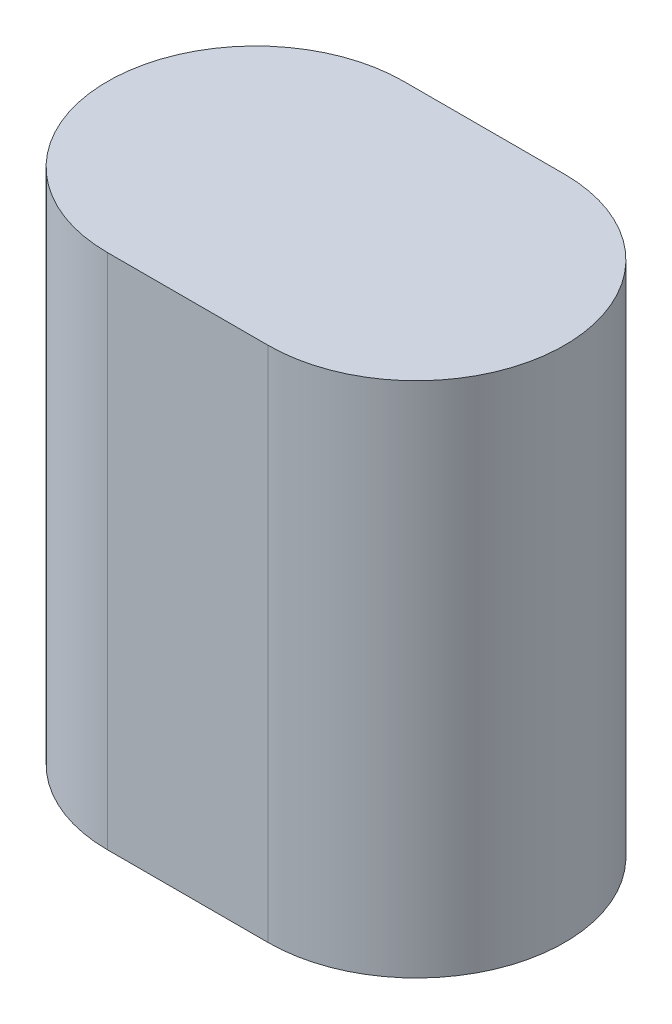
SolidWorks part; units mm, degrees
ref_plane "Front Plane" through (0, 0, 0) normal (0, 0, 1) x (1, 0, 0)
ref_plane "Top Plane" through (0, 0, 0) normal (0, 1, 0) x (1, 0, 0)
ref_plane "Right Plane" through (0, 0, 0) normal (1, 0, 0) x (0, 0, -1)
sketch "Sketch3" plane through (0, 0, 0) normal (0, 1, 0) x (1, 0, 0)
  line L0 (-8, 0) -> (8, 0) construction
  line L1 (-8, 14.7556) -> (8, 14.7557)
  line L2 (-8, -14.7556) -> (8, -14.7556)
  arc A0 (-8, 14.7556) -> (-8, -14.7556) centre (-8, 0) ccw
  arc A1 (8, -14.7556) -> (8, 14.7557) centre (8, 0) ccw
  point P2 (0, 0)
  dimension "D2" = 16
  dimension "D1" = 29.5113
extrude "Boss-Extrude1" add sketch "Sketch3" along normal blind 51.5
